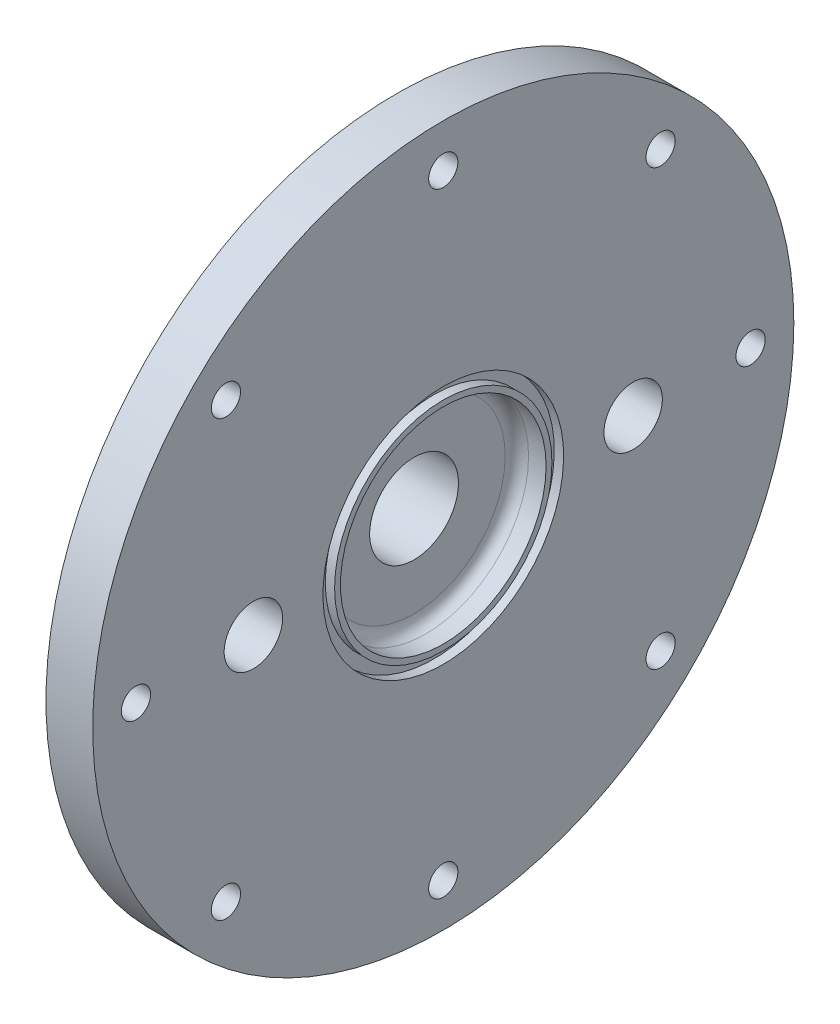
SolidWorks part; units mm, degrees
ref_plane "Front Plane" through (0, 0, 0) normal (0, 0, 1) x (1, 0, 0)
ref_plane "Top Plane" through (0, 0, 0) normal (0, 1, 0) x (1, 0, 0)
ref_plane "Right Plane" through (0, 0, 0) normal (1, 0, 0) x (0, 0, -1)
sketch "Sketch1" plane through (0, 0, 0) normal (0, 0, 1) x (1, 0, 0)
  line L1 (0, 76.2) -> (-10.16, 76.2)
  line L2 (-10.16, 76.2) -> (-10.16, 21.082)
  line L3 (-15.24, 16.002) -> (-31.75, 16.002)
  line L4 (-31.75, 16.002) -> (-31.75, 9.652)
  line L5 (-31.75, 9.652) -> (-6.35, 9.652)
  line L6 (-6.35, 9.652) -> (-6.35, 19.812)
  line L7 (-3.81, 22.352) -> (0, 22.352)
  line L8 (0, 22.352) -> (0, 76.2)
  line L9 (0, 0) -> (-31.75, 0) construction
  line L10 (-31.75, 0) -> (-31.75, 9.652) construction
  arc A0 (-10.16, 21.082) -> (-15.24, 16.002) centre (-15.24, 21.082) cw
  arc A2 (-6.35, 19.812) -> (-3.81, 22.352) centre (-3.81, 19.812) cw
  dimension "Top Part Outer Fillet" = 5.08
  dimension "LOX Manifold Fillet" = 2.54
  dimension "LOX Valve Thickness" = 6.35
  dimension "Distance between Manifold and Outer Surface" = 3.81
  dimension "LOX Valve Radius" = 9.652
  dimension "Depth of LOX Manifold" = 6.35
  dimension "Valve Entry Depth" = 25.4
  dimension "Comp Radius" = 76.2
  dimension "Manifold Radius" = 22.352
revolve "Revolve1" add sketch "Sketch1" angle 360 about L9
sketch "Sketch2" plane through (0, 0, 0) normal (1, 0, 0) x (0, 0, -1)
  line L0 (-41.275, 0) -> (41.275, 0) construction
  circle A0 centre (41.275, 0) radius 6.35
  circle A1 centre (-41.275, 0) radius 6.35
  point P8 (0, 0)
  dimension "Valve Diameter" = 12.7
  dimension "Distance of Prop Valves" = 82.55
extrude "Cut-Extrude1" cut sketch "Sketch2" against normal through all and the other way through all
sketch "Sketch3" plane through (0, 0, 0) normal (1, 0, 0) x (0, 0, -1)
  line L0 (0, 0) -> (66.802, 0) construction
  circle A0 centre (66.802, 0) radius 3.175
  dimension "Screw Hole Diameter" = 6.35
  dimension "Distance of Screw Holes from Center" = 66.802
extrude "Cut-Extrude2" cut sketch "Sketch3" against normal through all
pattern_circular "CirPattern1" count 8 over 360 about axis through (0, 0, 0) along (1, 0, 0) of "Cut-Extrude2"
sketch "Sketch4" plane through (0, 0, 0) normal (0, 0, 1) x (1, 0, 0)
  line L0 (0, -76.2) -> (0, 76.2) construction
  line L1 (0, 23.622) -> (-2.032, 23.622)
  line L2 (0, 23.622) -> (0, 26.162)
  line L3 (0, 26.162) -> (-2.032, 26.162)
  line L4 (-2.032, 23.622) -> (-2.032, 26.162)
  line L5 (0, 0) -> (-31.75, 0) construction
  line L6 (-31.75, 16.002) -> (-31.75, -16.002) construction
  dimension "Top ORing Width" = 2.54
  dimension "Top ORing Depth" = 2.032
  dimension "Top ORing Radius" = 23.622
revolve "Cut-Revolve1" cut sketch "Sketch4" angle 360 about L5
